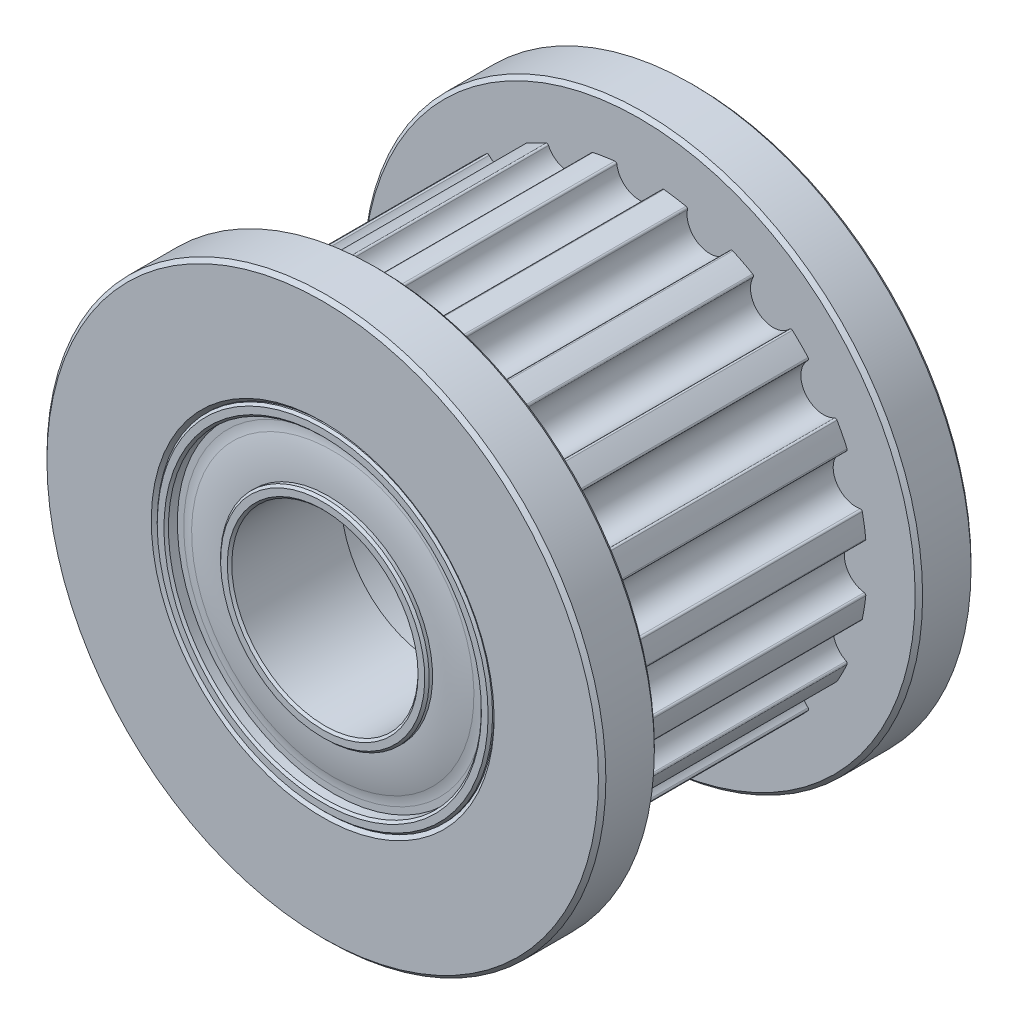
SolidWorks part; units mm, degrees
ref_plane "Front" through (0, 0, 0) normal (0, 0, 1) x (1, 0, 0)
ref_plane "Top" through (0, 0, 0) normal (0, 1, 0) x (1, 0, 0)
ref_plane "Right" through (0, 0, 0) normal (1, 0, 0) x (0, 0, -1)
sketch "Sketch1" plane through (0, 0, 0) normal (1, 0, 0) x (0, 0, -1)
  line L0 (-5, 0) -> (5, 0) construction
  line L1 (5, 7.5) -> (5, -7.5) construction
  line L2 (5, 7.5) -> (3.5, 7.5) construction
  line L3 (5, 2.5) -> (5, -2.5) construction
  line L4 (5, 6.11) -> (5, -6.11) construction
  line L5 (3, 0) -> (-3, 0) construction
  line L6 (3.5, 7.5) -> (3.5, 6.11) construction
  line L7 (5, 4.5) -> (2, 4.5) construction
  line L8 (2, 4.5) -> (2, 2.5) construction
  line L9 (2, 2.5) -> (5, 2.5) construction
  line L10 (5, 4.5) -> (5, -4.5) construction
  line L11 (-5, 0) -> (-5, 7.5) construction
  line L12 (-5, 7.5) -> (-3.5, 7.5) construction
  line L13 (-3.5, 7.5) -> (-3.5, 6.11) construction
  line L14 (-3.5, 6.11) -> (3.5, 6.11) construction
  line L15 (3.5, 6.11) -> (3.5, -6.11) construction
  line L16 (3.5, -6.11) -> (-3.5, -6.11) construction
  line L17 (-3.5, -6.11) -> (-3.5, 6.11) construction
  line L18 (0, -3.5) -> (0, 3.5) construction
  point P15 (5, 0)
  point P22 (3.5, 0)
  point P24 (-3, -6.11)
  point P25 (3, -6.11)
  point P29 (0, 0)
  dimension "Width" = 10
  dimension "OD" = 15
  dimension "ID" = 5
  dimension "Diameter" = 12.22
  dimension "Groove Depth" = 1.39
  dimension "For Maximum Belt Width" = 6
  dimension "For Shaft Diameter" = 5
  dimension "Bearing Diameter" = 9
  dimension "Bearing Width" = 3
  dimension "Inside Width" = 7
  dimension "Wall Thickness" = 1.5
  dimension "D1" = 7
sketch "Sketch5" plane through (0, 0, 0) normal (0, 0, 1) x (1, 0, 0)
  circle A0 centre (0, 0) radius 7.5 construction
  circle A1 centre (0, 0) radius 6.11 construction
  circle A2 centre (0, 0) radius 2.5 construction
  point P5 (0, 0)
  point P9 (-6.11, 0)
  point P10 (-7.5, 0)
  point P13 (0, 6.11)
sketch "Sketch2" plane through (0, 0, 0) normal (1, 0, 0) x (0, 0, -1)
  line L0 (5, 2.5) -> (2, 2.5)
  line L1 (5, 2.5) -> (5, 2.8)
  line L2 (5, 7.5) -> (5, -7.5) construction
  line L3 (5, 2.8) -> (4.7, 2.8) construction
  line L4 (4.85, 4.2) -> (4.85, 2.8) construction
  line L5 (5, 4.5) -> (2, 4.5)
  line L6 (4.7, 3.9) -> (4.7, 4.2)
  line L7 (5, 4.5) -> (5, 4.2)
  line L8 (5, 4.2) -> (4.7, 4.2)
  line L9 (4.7, 4.2) -> (4.7, 2.8) construction
  line L10 (2, 4.5) -> (2, 2.5)
  line L11 (4.85, 2.8) -> (5, 2.8)
  arc A0 (4.7, 3.9) -> (4.85, 2.8) centre (0.7417, 2.8) cw
  dimension "D1" = 0.3
revolve "Revolve1" add sketch "Sketch2" angle 360 about L0
chamfer "Chamfer2" distance 0.06 angle 45 4 edges at (0, -2.8, -5) (0, -2.5, -5) (0, -4.2, -5) (0, -4.5, -5)
fillet "Fillet2" radius 1 1 edges at (0, -3.9, -4.7)
mirror "Mirror1" about plane through (0, 0, 0) normal (0, 0, 1) of bodies 108
sketch "Sketch3" plane through (0, 0, 0) normal (1, 0, 0) x (0, 0, -1)
  line L0 (3.5, 7.5) -> (5, 7.5)
  line L1 (5, 7.5) -> (5, 4.5)
  line L2 (5, 7.5) -> (5, -7.5) construction
  line L3 (-5, 4.5) -> (-2, 4.5)
  line L4 (-2, 4.5) -> (-2, 3.5)
  line L5 (-2, 3.5) -> (2, 3.5)
  line L6 (2, 3.5) -> (2, 4.5)
  line L8 (2, 4.5) -> (5, 4.5)
  line L9 (3.5, 7.5) -> (3.5, 6.11)
  line L10 (3.5, 6.11) -> (-3.5, 6.11)
  line L11 (0, 6.11) -> (0, 4.5) construction
  line L12 (-5, 4.5) -> (5, 4.5) construction
  line L13 (-3.5, 7.5) -> (-3.5, 6.11)
  line L19 (-5, 7.5) -> (-5, 4.5)
  line L20 (-3.5, 7.5) -> (-5, 7.5)
revolve "Revolve2" add sketch "Sketch3" angle 360 about L0
chamfer "Chamfer1" distance 0.1 angle 45 6 edges at (0, -7.5, -5) (0, -7.5, -3.5) (0, -7.5, 3.5) (0, -7.5, 5) (0, -4.5, -5) (0, -4.5, 5)
sketch "Sketch4" plane through (0, 0, 0) normal (0, 0, 1) x (1, 0, 0)
  line L0 (-0.611, 6.11) -> (0.611, 6.11)
  line L1 (-0.611, 6.11) -> (-0.611, 5.554) construction
  line L2 (-0.611, 5.554) -> (0.611, 5.554) construction
  line L3 (0.611, 5.554) -> (0.611, 6.11) construction
  line L4 (0, 6.11) -> (0, 5.554) construction
  arc A0 (0.611, 6.11) -> (-0.611, 6.11) centre (0, 6.11) cw
  dimension "D1" = 0.556
  dimension "D3" = 1.222
extrude "Cut-Extrude1" cut sketch "Sketch4" against normal up to surface and the other way up to surface
fillet "Fillet1" radius 0.05 2 edges at (-0.6102, 6.0795, 0) (0.6102, 6.0795, 0)
pattern_circular "CirPattern3" count 20 over 360 about axis through (0, 0, 0) along (0, 0, 1) of "Cut-Extrude1", "Fillet1"
equation "\"D1@Sketch4\"=\"Groove Depth@Sketch1\"/2.5"
equation "\"D3@Sketch4\"=\"Diameter@Sketch1\"/10"
equation "\"D1@Sketch1\"=\"ID@Sketch1\"+2"
